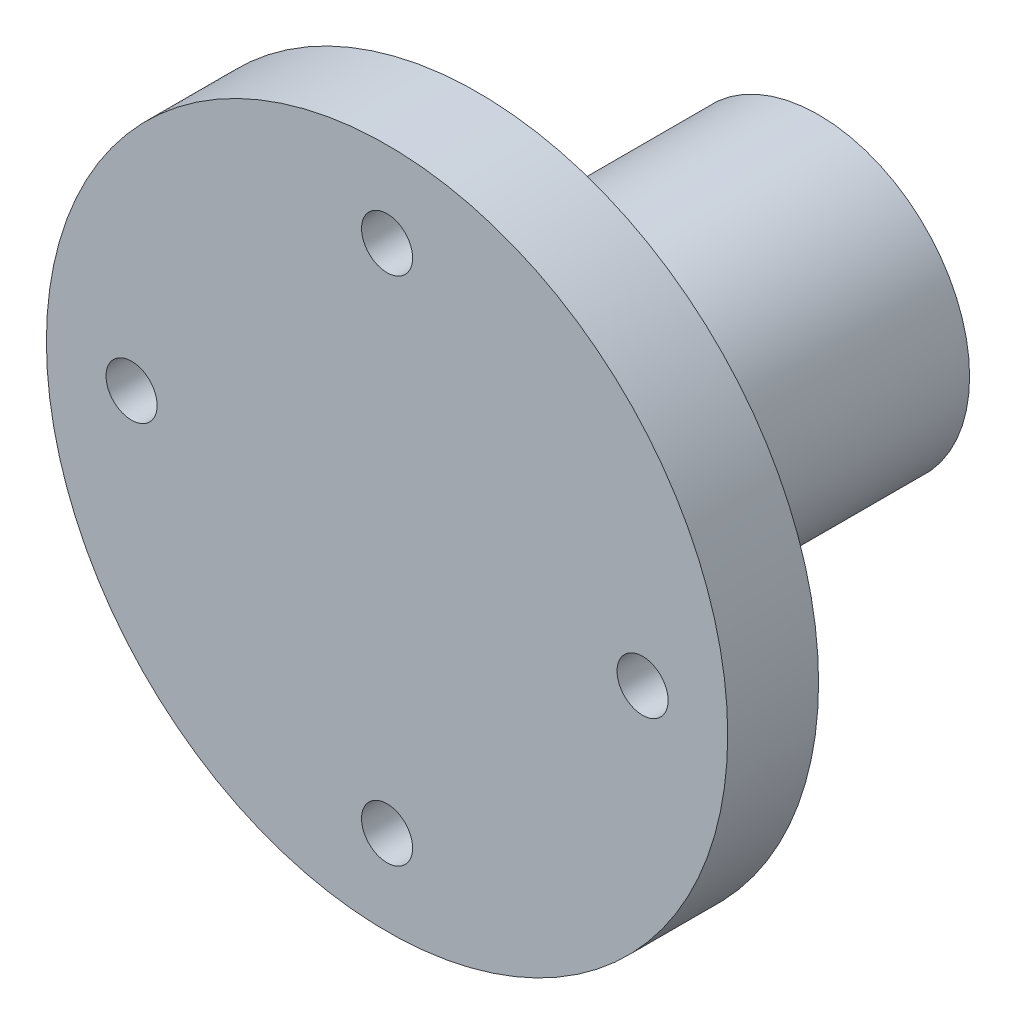
SolidWorks part; units mm, degrees
material "ABS"
ref_plane "Alzado" through (0, 0, 0) normal (0, 0, 1) x (1, 0, 0)
ref_plane "Planta" through (0, 0, 0) normal (0, 1, 0) x (1, 0, 0)
ref_plane "Vista lateral" through (0, 0, 0) normal (1, 0, 0) x (0, 0, -1)
sketch "Croquis1" plane through (0, 0, 0) normal (0, 0, 1) x (1, 0, 0)
  circle A0 centre (0, 0) radius 13.3
  dimension "D1" = 26.6
extrude "Saliente-Extruir1" add sketch "Croquis1" against normal blind 30
sketch "Croquis2" plane through (0, 0, 0) normal (0, 0, 1) x (1, 0, 0)
  circle A0 centre (0, 0) radius 22.5 construction
  circle A1 centre (0, 0) radius 30
  circle A2 centre (0, 22.5) radius 2.25
  circle A3 centre (22.5, 0) radius 2.25
  circle A4 centre (0, -22.5) radius 2.25
  circle A5 centre (-22.5, 0) radius 2.25
  dimension "D1" = 45
  dimension "D2" = 60
  dimension "D3" = 4.5
  dimension "D4" = 4
extrude "Saliente-Extruir2" add sketch "Croquis2" along normal blind 8
